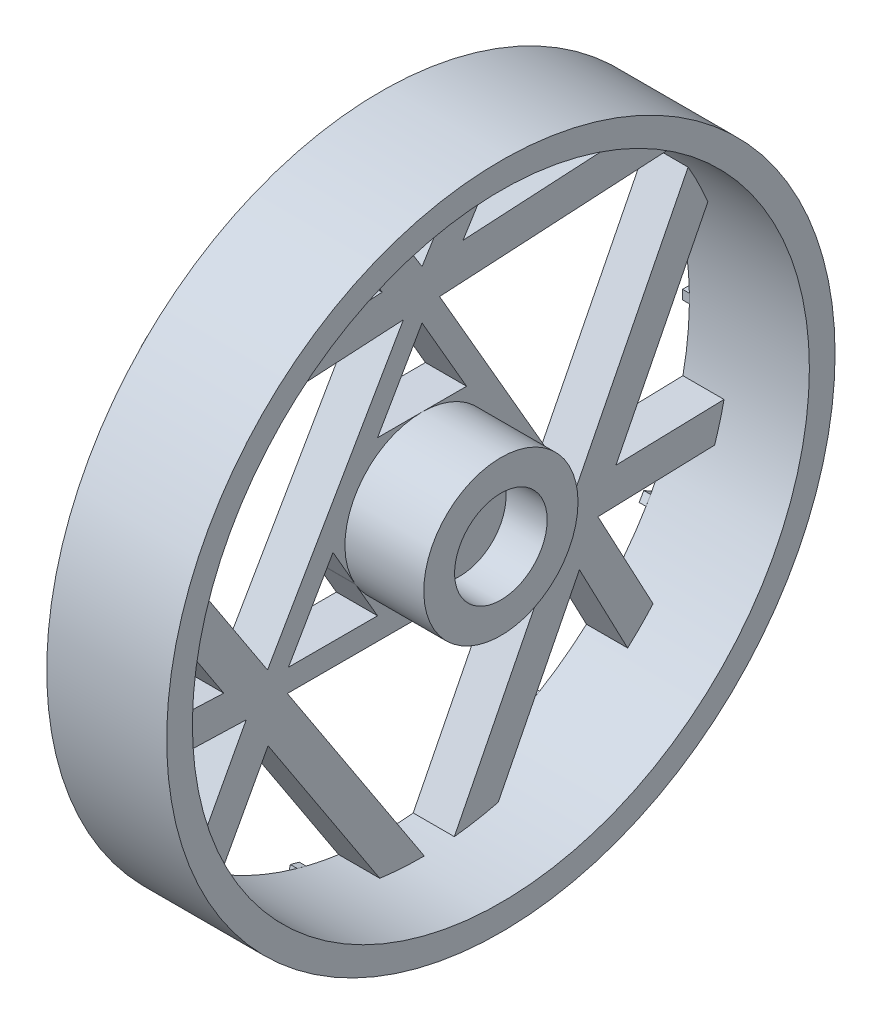
SolidWorks part; units mm, degrees
ref_plane "Front Plane" through (0, 0, 0) normal (0, 0, 1) x (1, 0, 0)
ref_plane "Top Plane" through (0, 0, 0) normal (0, 1, 0) x (1, 0, 0)
ref_plane "Right Plane" through (0, 0, 0) normal (1, 0, 0) x (0, 0, -1)
sketch "Sketch1" plane through (0, 0, 0) normal (1, 0, 0) x (0, 0, -1)
  line L0 (0, 0) -> (0, 45) construction
  line L1 (38.9711, -22.5) -> (0, 45)
  line L2 (0, 45) -> (-38.9711, -22.5)
  line L3 (-38.9711, -22.5) -> (38.9711, -22.5)
  line L4 (50.1934, -28.9792) -> (0, 57.9583)
  line L5 (0, 57.9583) -> (-50.1934, -28.9792)
  line L6 (-50.1934, -28.9792) -> (50.1934, -28.9792)
  line L7 (0, 0) -> (0, 57.9583) construction
  circle A0 centre (0, 0) radius 22.5 construction
  dimension "D1" = 45
sketch "Sketch4" plane through (0, 0, 0) normal (1, 0, 0) x (0, 0, -1)
  circle A0 centre (0, 0) radius 22.5
  circle A1 centre (0, 0) radius 97.5
  circle A2 centre (0, 0) radius 90
  dimension "D1" = 45
  dimension "D2" = 180
  dimension "D3" = 195
extrude "Boss-Extrude1" add sketch "Sketch4" along normal blind 35 contours A1 A2 | A0
extrude "Boss-Extrude2" add sketch "Sketch1" along normal blind 12
sketch "Sketch8" plane through (0, 0, 0) normal (1, 0, 0) x (0, 0, -1)
  line L1 (81.5773, 53.3985) -> (-87.0331, 43.9488)
  line L2 (-87.0331, 43.9488) -> (5.4558, -97.3472)
  line L3 (5.4558, -97.3472) -> (81.5773, 53.3985)
  line L4 (74.0789, 63.3922) -> (-80.6983, 54.7178)
  line L5 (-91.9387, 32.4581) -> (-7.0378, -97.2457)
  line L6 (17.8598, -95.8503) -> (87.7361, 42.5279)
  circle A0 centre (0, 0) radius 97.5 construction
  arc A1 (-7.0378, -97.2457) -> (17.8598, -95.8503) centre (0, 0) ccw
  arc A2 (74.0789, 63.3922) -> (87.7361, 42.5279) centre (0, 0) cw
  arc A3 (-80.6983, 54.7178) -> (-91.9387, 32.4581) centre (0, 0) ccw
  circle A4 centre (0, 0) radius 97.5 construction
  point P1 (-107.1951, 55.7654)
  point P11 (-108.5478, 53.157)
extrude "Boss-Extrude3" add sketch "Sketch8" along normal blind 12 contours L2 A3 L5 A1 | A2 L3 A1 L6 | L4 A3 L1 A2
sketch "Sketch10" plane through (0, 0, 0) normal (1, 0, 0) x (0, 0, -1)
  line L0 (0, 0) -> (0, 90) construction
  line L2 (-5.4486, 48.5211) -> (0, 59.2405) construction
  line L4 (0, 59.2405) -> (-17.9586, 88.1901)
  line L6 (-28.1357, 85.4891) -> (-5.4486, 48.5211)
  line L7 (-5.4486, 48.5211) -> (0, 59.2405)
  line L8 (64.4188, 62.8508) -> (-71.0382, 55.2592) construction
  line L9 (0, 59.2405) -> (17.9586, 88.1901)
  line L10 (5.107, 49.1127) -> (0, 59.2405)
  line L11 (28.1357, 85.4891) -> (5.107, 49.1127)
  circle A0 centre (0, 0) radius 90 construction
  arc A1 (-17.9586, 88.1901) -> (-28.1357, 85.4891) centre (-17.6722, 66.587) ccw
  arc A2 (17.9586, 88.1901) -> (28.1357, 85.4891) centre (17.6722, 66.587) cw
extrude "Boss-Extrude8" add sketch "Sketch10" along normal blind 12 contours A2 L9 L10 L11 | L4 A1 L6 L7
sketch "Sketch19" plane through (0, 0, 0) normal (-1, 0, 0) x (0, 0, 1)
  line L0 (0, 0) -> (0, 90) construction
  arc A0 (-28.1357, 85.4891) -> (-64.4188, 62.8508) centre (0, 0) ccw construction
pattern_circular "CirPattern1" count 3 over 360 about axis through (0, 0, 0) along (1, 0, 0) of "Boss-Extrude8"
sketch "Sketch21" plane through (35, 0, 0) normal (1, 0, 0) x (0, 0, -1)
  circle A0 centre (0, 0) radius 13.5
extrude "Cut-Extrude3" cut sketch "Sketch21" against normal blind 12
sketch "Sketch22" plane through (0, 0, 0) normal (-1, 0, 0) x (0, 0, 1)
  circle A0 centre (0, 0) radius 90
sketch "Sketch23" plane through (0, 0, 0) normal (-1, 0, 0) x (0, 0, 1)
  line L0 (-12.9896, 22.5013) -> (12.9896, 22.5013)
  line L2 (0, 45) -> (38.9711, -22.5) construction
  line L3 (12.9896, 22.5013) -> (25.9808, 0)
  line L4 (25.9808, 0) -> (12.9896, -22.5)
  line L5 (38.9711, -22.5) -> (-38.9711, -22.5) construction
  line L6 (12.9896, -22.5) -> (-12.9896, -22.5)
  line L7 (-12.9896, -22.5) -> (-25.9804, 0.0007)
  line L8 (-38.9711, -22.5) -> (0, 45) construction
  line L9 (-25.9804, 0.0007) -> (-12.9896, 22.5013)
  point P3 (0, 22.5013)
extrude "Boss-Extrude9" add sketch "Sketch23" against normal blind 12
sketch "Sketch24" plane through (0, 0, 0) normal (-1, 0, 0) x (0, 0, 1)
  circle A0 centre (0, 0) radius 11.8238
  circle A1 centre (0, 0) radius 13.9837
  circle A2 centre (10.4592, 16.3481) radius 1.2445
  circle A3 centre (-4.1641, 18.9556) radius 1.2445
  circle A4 centre (-16.3481, 10.4592) radius 1.2445
  circle A5 centre (-18.9556, -4.1641) radius 1.2445
  circle A6 centre (-10.4592, -16.3481) radius 1.2445
  circle A7 centre (4.1641, -18.9556) radius 1.2445
  circle A8 centre (16.3481, -10.4592) radius 1.2445
  circle A9 centre (18.9556, 4.1641) radius 1.2445
  point P22 (0, 0)
  dimension "D1" = 8
extrude "Cut-Extrude4" cut sketch "Sketch24" against normal blind 4
sketch "Sketch25" plane through (0, 0, 0) normal (-1, 0, 0) x (0, 0, 1)
  line L0 (24.7509, 86.5297) -> (25.9725, 91.0889)
  line L1 (1.512, 89.9873) -> (-1.1809, 89.9873)
  line L2 (1.512, 89.9873) -> (1.512, 94.7073)
  line L3 (1.512, 94.7073) -> (-1.1809, 94.7073)
  line L4 (-1.1809, 89.9873) -> (-1.1809, 94.7073)
  line L5 (24.7509, 86.5297) -> (22.1498, 87.2267)
  line L6 (22.1498, 87.2267) -> (23.3714, 91.7859)
  line L7 (25.9725, 91.0889) -> (23.3714, 91.7859)
  line L8 (46.3031, 77.1753) -> (48.6631, 81.263)
  line L9 (46.3031, 77.1753) -> (43.971, 78.5217)
  line L10 (43.971, 78.5217) -> (46.331, 82.6094)
  line L11 (48.6631, 81.263) -> (46.331, 82.6094)
  line L12 (64.6998, 62.5615) -> (68.0373, 65.8991)
  line L13 (64.6998, 62.5615) -> (62.7956, 64.4657)
  line L14 (62.7956, 64.4657) -> (66.1332, 67.8032)
  line L15 (68.0373, 65.8991) -> (66.1332, 67.8032)
  line L16 (78.6873, 43.6842) -> (82.7749, 46.0443)
  line L17 (78.6873, 43.6842) -> (77.3408, 46.0163)
  line L18 (77.3408, 46.0163) -> (81.4285, 48.3764)
  line L19 (82.7749, 46.0443) -> (81.4285, 48.3764)
  line L20 (87.3124, 21.83) -> (91.8716, 23.0516)
  line L21 (87.3124, 21.83) -> (86.6154, 24.4311)
  line L22 (86.6154, 24.4311) -> (91.1746, 25.6527)
  line L23 (91.8716, 23.0516) -> (91.1746, 25.6527)
  line L24 (89.9873, -1.512) -> (94.7073, -1.512)
  line L25 (89.9873, -1.512) -> (89.9873, 1.1809)
  line L26 (89.9873, 1.1809) -> (94.7073, 1.1809)
  line L27 (94.7073, -1.512) -> (94.7073, 1.1809)
  line L28 (86.5297, -24.7509) -> (91.0889, -25.9725)
  line L29 (86.5297, -24.7509) -> (87.2267, -22.1498)
  line L30 (87.2267, -22.1498) -> (91.7859, -23.3714)
  line L31 (91.0889, -25.9725) -> (91.7859, -23.3714)
  line L32 (77.1753, -46.3031) -> (81.263, -48.6631)
  line L33 (77.1753, -46.3031) -> (78.5217, -43.971)
  line L34 (78.5217, -43.971) -> (82.6094, -46.331)
  line L35 (81.263, -48.6631) -> (82.6094, -46.331)
  line L36 (62.5615, -64.6998) -> (65.8991, -68.0373)
  line L37 (62.5615, -64.6998) -> (64.4657, -62.7956)
  line L38 (64.4657, -62.7956) -> (67.8032, -66.1332)
  line L39 (65.8991, -68.0373) -> (67.8032, -66.1332)
  line L40 (43.6842, -78.6873) -> (46.0443, -82.7749)
  line L41 (43.6842, -78.6873) -> (46.0163, -77.3408)
  line L42 (46.0163, -77.3408) -> (48.3764, -81.4285)
  line L43 (46.0443, -82.7749) -> (48.3764, -81.4285)
  line L44 (21.83, -87.3124) -> (23.0516, -91.8716)
  line L45 (21.83, -87.3124) -> (24.4311, -86.6154)
  line L46 (24.4311, -86.6154) -> (25.6527, -91.1746)
  line L47 (23.0516, -91.8716) -> (25.6527, -91.1746)
  line L48 (-1.512, -89.9873) -> (-1.512, -94.7073)
  line L49 (-1.512, -89.9873) -> (1.1809, -89.9873)
  line L50 (1.1809, -89.9873) -> (1.1809, -94.7073)
  line L51 (-1.512, -94.7073) -> (1.1809, -94.7073)
  line L52 (-24.7509, -86.5297) -> (-25.9725, -91.0889)
  line L53 (-24.7509, -86.5297) -> (-22.1498, -87.2267)
  line L54 (-22.1498, -87.2267) -> (-23.3714, -91.7859)
  line L55 (-25.9725, -91.0889) -> (-23.3714, -91.7859)
  line L56 (-46.3031, -77.1753) -> (-48.6631, -81.263)
  line L57 (-46.3031, -77.1753) -> (-43.971, -78.5217)
  line L58 (-43.971, -78.5217) -> (-46.331, -82.6094)
  line L59 (-48.6631, -81.263) -> (-46.331, -82.6094)
  line L60 (-64.6998, -62.5615) -> (-68.0373, -65.8991)
  line L61 (-64.6998, -62.5615) -> (-62.7956, -64.4657)
  line L62 (-62.7956, -64.4657) -> (-66.1332, -67.8032)
  line L63 (-68.0373, -65.8991) -> (-66.1332, -67.8032)
  line L64 (-78.6873, -43.6842) -> (-82.7749, -46.0443)
  line L65 (-78.6873, -43.6842) -> (-77.3408, -46.0163)
  line L66 (-77.3408, -46.0163) -> (-81.4285, -48.3764)
  line L67 (-82.7749, -46.0443) -> (-81.4285, -48.3764)
  line L68 (-87.3124, -21.83) -> (-91.8716, -23.0516)
  line L69 (-87.3124, -21.83) -> (-86.6154, -24.4311)
  line L70 (-86.6154, -24.4311) -> (-91.1746, -25.6527)
  line L71 (-91.8716, -23.0516) -> (-91.1746, -25.6527)
  line L72 (-89.9873, 1.512) -> (-94.7073, 1.512)
  line L73 (-89.9873, 1.512) -> (-89.9873, -1.1809)
  line L74 (-89.9873, -1.1809) -> (-94.7073, -1.1809)
  line L75 (-94.7073, 1.512) -> (-94.7073, -1.1809)
  line L76 (-86.5297, 24.7509) -> (-91.0889, 25.9725)
  line L77 (-86.5297, 24.7509) -> (-87.2267, 22.1498)
  line L78 (-87.2267, 22.1498) -> (-91.7859, 23.3714)
  line L79 (-91.0889, 25.9725) -> (-91.7859, 23.3714)
  line L80 (-77.1753, 46.3031) -> (-81.263, 48.6631)
  line L81 (-77.1753, 46.3031) -> (-78.5217, 43.971)
  line L82 (-78.5217, 43.971) -> (-82.6094, 46.331)
  line L83 (-81.263, 48.6631) -> (-82.6094, 46.331)
  line L84 (-62.5615, 64.6998) -> (-65.8991, 68.0373)
  line L85 (-62.5615, 64.6998) -> (-64.4657, 62.7956)
  line L86 (-64.4657, 62.7956) -> (-67.8032, 66.1332)
  line L87 (-65.8991, 68.0373) -> (-67.8032, 66.1332)
  line L88 (-43.6842, 78.6873) -> (-46.0443, 82.7749)
  line L89 (-43.6842, 78.6873) -> (-46.0163, 77.3408)
  line L90 (-46.0163, 77.3408) -> (-48.3764, 81.4285)
  line L91 (-46.0443, 82.7749) -> (-48.3764, 81.4285)
  line L92 (-21.83, 87.3124) -> (-23.0516, 91.8716)
  line L93 (-21.83, 87.3124) -> (-24.4311, 86.6154)
  line L94 (-24.4311, 86.6154) -> (-25.6527, 91.1746)
  line L95 (-23.0516, 91.8716) -> (-25.6527, 91.1746)
  circle A0 centre (0, 0) radius 90 construction
  point P101 (0, 0)
  dimension "D1" = 24
extrude "Boss-Extrude10" add sketch "Sketch25" along normal blind 2
sketch "Sketch16" plane through (0, 0, 0) normal (1, 0, 0) x (0, 0, -1)
  circle A0 centre (0, 0) radius 32.9625
